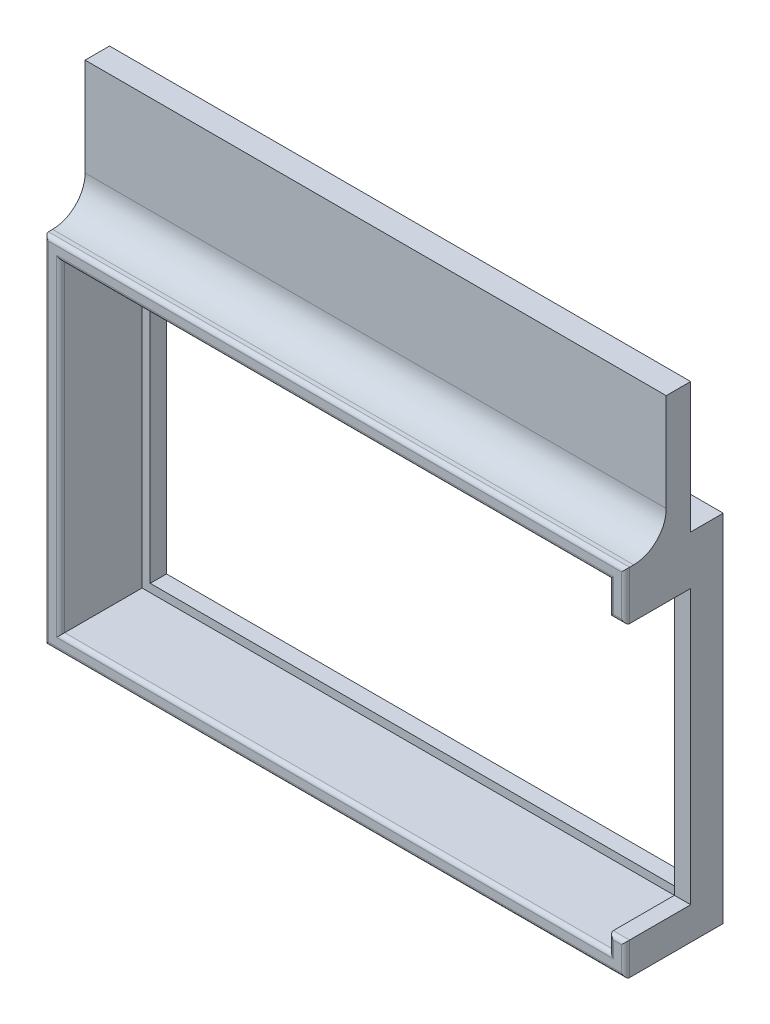
SolidWorks part; units mm, degrees
ref_plane "Plan de face" through (0, 0, 0) normal (0, 0, 1) x (1, 0, 0)
ref_plane "Plan de dessus" through (0, 0, 0) normal (0, 1, 0) x (1, 0, 0)
ref_plane "Plan de droite" through (0, 0, 0) normal (1, 0, 0) x (0, 0, -1)
sketch "Esquisse1" plane through (0, 0, 0) normal (0, 0, 1) x (1, 0, 0)
  line L1 (0, 0) -> (35.68, 0)
  line L2 (0, 0) -> (0, 21.82)
  line L3 (0, 21.82) -> (35.68, 21.82)
  line L4 (35.68, 0) -> (35.68, 21.82)
extrude "Boss.-Extru.1" add sketch "Esquisse1" along normal blind 6
sketch "Esquisse2" plane through (0, 0, 6) normal (0, 0, 1) x (1, 0, 0)
  line L0 (0, 0) -> (35.68, 0) construction
  line L1 (1, 1) -> (34.68, 1)
  line L2 (1, 1) -> (1, 20.82)
  line L3 (1, 20.82) -> (34.68, 20.82)
  line L4 (34.68, 1) -> (34.68, 20.82)
  line L5 (0, 21.82) -> (0, 0) construction
  line L6 (35.68, 21.82) -> (0, 21.82) construction
  line L7 (35.68, 0) -> (35.68, 21.82) construction
  dimension "D1" = 1
  dimension "D2" = 1
  dimension "D3" = 1
  dimension "D4" = 1
extrude "Enlèv. mat.-Extru.1" cut sketch "Esquisse2" against normal blind 5
sketch "Esquisse3" plane through (0, 0, 1) normal (0, 0, 1) x (1, 0, 0)
  line L1 (1.5, 1.5) -> (34.18, 1.5)
  line L2 (1.5, 1.5) -> (1.5, 20.32)
  line L3 (1.5, 20.32) -> (34.18, 20.32)
  line L4 (34.18, 1.5) -> (34.18, 20.32)
  line L5 (1, 1) -> (34.68, 1) construction
  line L6 (1, 20.82) -> (1, 1) construction
  line L7 (34.68, 1) -> (34.68, 20.82) construction
  line L8 (34.68, 20.82) -> (1, 20.82) construction
  dimension "D1" = 0.5
  dimension "D2" = 0.5
  dimension "D3" = 0.5
  dimension "D4" = 0.5
extrude "Enlèv. mat.-Extru.2" cut sketch "Esquisse3" against normal through all
sketch "Esquisse4" plane through (35.68, 0, 0) normal (1, 0, 0) x (0, 0, -1)
  line L0 (-6, 0) -> (-6, 21.82) construction
  line L1 (-6, 18.82) -> (-2, 18.82)
  line L2 (-6, 18.82) -> (-6, 2)
  line L3 (-6, 2) -> (-2, 2)
  line L4 (-2, 18.82) -> (-2, 2)
  line L5 (-6, 0) -> (0, 0) construction
  line L6 (-6, 21.82) -> (0, 21.82) construction
  line L7 (0, 0) -> (0, 21.82) construction
  dimension "D1" = 0
  dimension "D2" = 2
  dimension "D3" = 3
  dimension "D4" = 2
extrude "Enlèv. mat.-Extru.3" cut sketch "Esquisse4" against normal blind 5
sketch "Esquisse5" plane through (0, 0, 1) normal (0, 0, 1) x (1, 0, 0)
  line L0 (35.68, 21.82) -> (0, 21.82) construction
  line L1 (34.18, 20.82) -> (34.68, 20.82)
  line L2 (34.18, 20.82) -> (34.18, 20.32)
  line L3 (34.18, 20.32) -> (34.68, 20.32)
  line L4 (34.68, 20.82) -> (34.68, 20.32)
  line L5 (35.68, 2) -> (35.68, 18.82) construction
  line L6 (34.18, 20.32) -> (1.5, 20.32) construction
  line L7 (34.18, 1.5) -> (34.18, 20.32) construction
  dimension "D1" = 1
  dimension "D2" = 1
  dimension "D3" = 0
  dimension "D4" = 0
sketch "Esquisse6" plane through (0, 0, 6) normal (0, 0, 1) x (1, 0, 0)
  line L0 (0, 21.82) -> (0, 0) construction
  line L1 (0, 21.82) -> (35.68, 21.82)
  line L2 (0, 21.82) -> (0, 29.82)
  line L3 (0, 29.82) -> (35.68, 29.82)
  line L4 (35.68, 21.82) -> (35.68, 29.82)
  line L5 (35.68, 2) -> (35.68, 18.82) construction
  line L6 (35.68, 21.82) -> (0, 21.82) construction
  dimension "D1" = 0
  dimension "D2" = 0
  dimension "D3" = 8
  dimension "D4" = 0
extrude "Boss.-Extru.2" add sketch "Esquisse6" against normal blind 4
sketch "Esquisse7" plane through (0, 0, 6) normal (0, 0, 1) x (1, 0, 0)
  line L0 (35.68, 29.82) -> (0, 29.82) construction
  line L1 (0, 29.82) -> (35.68, 29.82)
  line L2 (0, 29.82) -> (0, 21.82)
  line L3 (0, 21.82) -> (35.68, 21.82)
  line L4 (35.68, 29.82) -> (35.68, 21.82)
  line L5 (0, 29.82) -> (0, 0) construction
  line L6 (35.68, 18.82) -> (35.68, 29.82) construction
  line L8 (34.68, 20.82) -> (1, 20.82) construction
  dimension "D1" = 0
  dimension "D2" = 0
  dimension "D3" = 0
  dimension "D4" = 1
  dimension "D5" = 8
extrude "Enlèv. mat.-Extru.12" cut sketch "Esquisse7" against normal blind 2.5
fillet "Congé1" radius 2 1 edges at (17.84, 21.82, 3.5)
fillet "Congé2" radius 0.25 12 edges at (35.18, 18.82, 6) (34.68, 19.82, 6) (17.84, 20.82, 6) (1, 10.91, 6) (17.84, 1, 6) (34.68, 1.5, 6) (35.18, 2, 6) (35.68, 1, 6) (17.84, 0, 6) (0, 10.91, 6) (17.84, 21.82, 6) (35.68, 20.32, 6)
